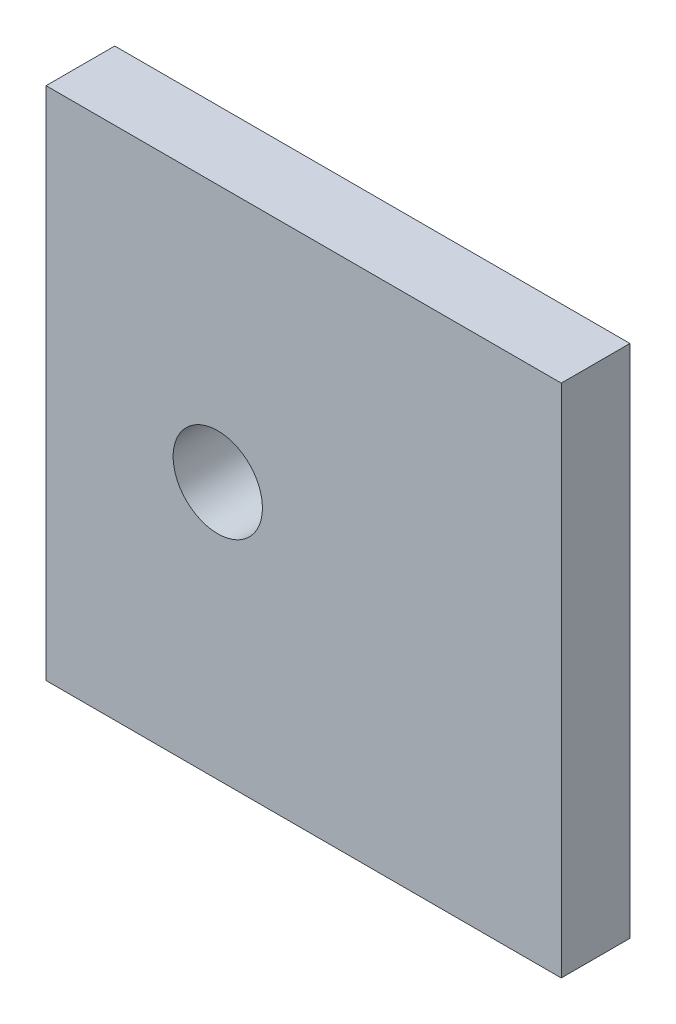
SolidWorks part; units mm, degrees
ref_plane "Front Plane" through (0, 0, 0) normal (0, 0, 1) x (1, 0, 0)
ref_plane "Top Plane" through (0, 0, 0) normal (0, 1, 0) x (1, 0, 0)
ref_plane "Right Plane" through (0, 0, 0) normal (1, 0, 0) x (0, 0, -1)
sketch "Sketch1" plane through (0, 0, 0) normal (0, 0, 1) x (1, 0, 0)
  line L1 (0, 0) -> (150, 0)
  line L2 (0, 0) -> (0, 150)
  line L3 (0, 150) -> (150, 150)
  line L4 (150, 0) -> (150, 150)
  dimension "D1" = 150
  dimension "D2" = 150
extrude "Extrude1" add sketch "Sketch1" along normal blind 20
sketch "Sketch2" plane through (0, 0, 20) normal (0, 0, 1) x (1, 0, 0)
  line L0 (0, 150) -> (0, 0) construction
  line L1 (150, 150) -> (0, 150) construction
  circle A0 centre (50, 75) radius 13
  dimension "D3" = 26
  dimension "D1" = 50
  dimension "D2" = 75
extrude "Cut-Extrude1" cut sketch "Sketch2" against normal through all
